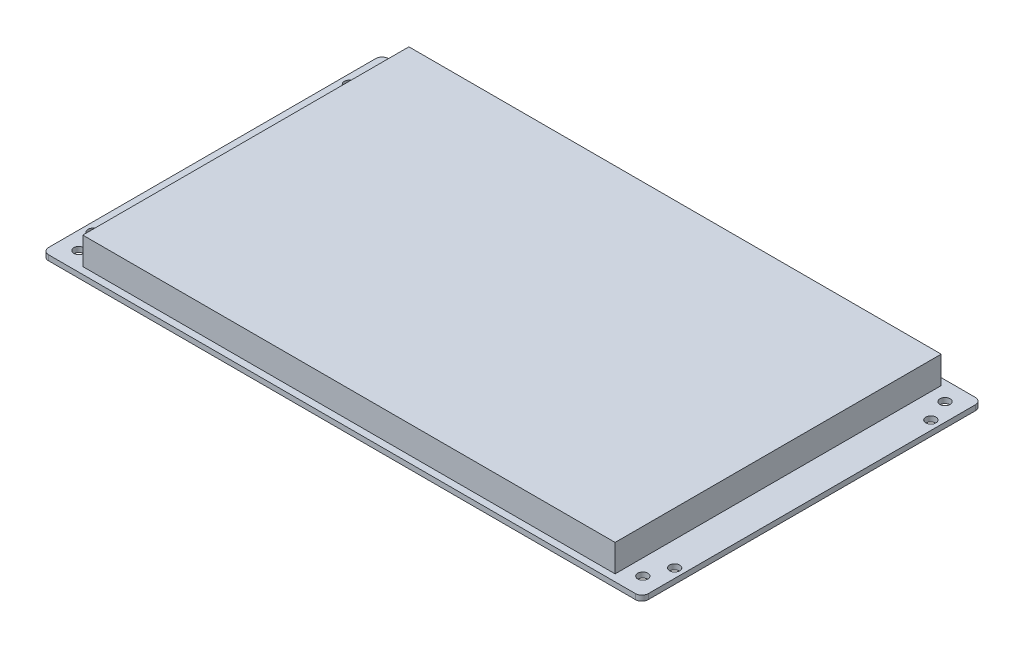
SolidWorks part; units mm, degrees
material "AÇO 1020"
ref_plane "Front Plane" through (0, 0, 0) normal (0, 0, 1) x (1, 0, 0)
ref_plane "Top Plane" through (0, 0, 0) normal (0, 1, 0) x (1, 0, 0)
ref_plane "Right Plane" through (0, 0, 0) normal (1, 0, 0) x (0, 0, -1)
sketch "Sketch1" plane through (0, 0, 0) normal (0, 1, 0) x (1, 0, 0)
  line L1 (93.5, 53) -> (-93.5, 53)
  line L2 (93.5, 53) -> (93.5, -53)
  line L3 (93.5, -53) -> (-93.5, -53)
  line L4 (-93.5, 53) -> (-93.5, -53)
  line L5 (0, -53) -> (0, 53) construction
  line L6 (93.5, 0) -> (-93.5, 0) construction
  point P0 (0, 0)
  dimension "D1" = 187
  dimension "D2" = 106
extrude "Extrude1" add sketch "Sketch1" along normal blind 1.64
sketch "Sketch2" plane through (0, 1.64, 0) normal (0, 1, 0) x (1, 0, 0)
  line L1 (83, 50.85) -> (-83, 50.85)
  line L2 (83, 50.85) -> (83, -50.85)
  line L3 (83, -50.85) -> (-83, -50.85)
  line L4 (-83, 50.85) -> (-83, -50.85)
  line L5 (0, -50.85) -> (0, 50.85) construction
  line L6 (83, 0) -> (-83, 0) construction
  point P0 (0, 0)
  dimension "D1" = 101.7
  dimension "D2" = 166
extrude "Extrude2" add sketch "Sketch2" along normal blind 8.5 separate body
fillet "Fillet1" radius 2 4 edges at (-93.5, 0.82, -53) (-93.5, 0.82, 53) (93.5, 0.82, 53) (93.5, 0.82, -53)
sketch "Sketch3" plane through (0, 1.64, 0) normal (0, 1, 0) x (1, 0, 0)
  line L0 (0, 0) -> (93.5, 0) construction
  line L1 (93.5, -51) -> (93.5, 51) construction
  line L2 (93.5, 0) -> (0, 53) construction
  line L3 (91.5, 53) -> (-91.5, 53) construction
  line L4 (0, 53) -> (0, -53) construction
  line L5 (-91.5, -53) -> (91.5, -53) construction
  line L11 (-93.5, 51) -> (-93.5, -51) construction
  circle A0 centre (87.925, 47.125) radius 1.575
  circle A1 centre (90.675, 39.95) radius 1.575
  circle A2 centre (90.675, -39.95) radius 1.575
  circle A3 centre (87.925, -47.125) radius 1.575
  circle A4 centre (-87.925, -47.125) radius 1.575
  circle A5 centre (-90.675, -39.95) radius 1.575
  circle A6 centre (-87.925, 47.125) radius 1.575
  circle A7 centre (-90.675, 39.95) radius 1.575
  point P27 (0, 0)
  point P28 (0, 0)
  point P29 (0, 0)
  point P30 (0, 0)
  point P31 (0, 0)
  point P32 (0, 0)
  point P33 (-86.5086, 47.493)
  point P34 (0, 0)
  point P35 (0, 0)
  point P36 (0, 0)
  point P37 (0, 0)
  point P38 (0, 0)
  point P39 (0, 0)
  point P40 (0, 0)
  dimension "D1" = 3.15
  dimension "D2" = 4
  dimension "D3" = 76.75
  dimension "D4" = 4.3
  dimension "D5" = 1.25
extrude "Extrude3" cut sketch "Sketch3" against normal blind 8.5
